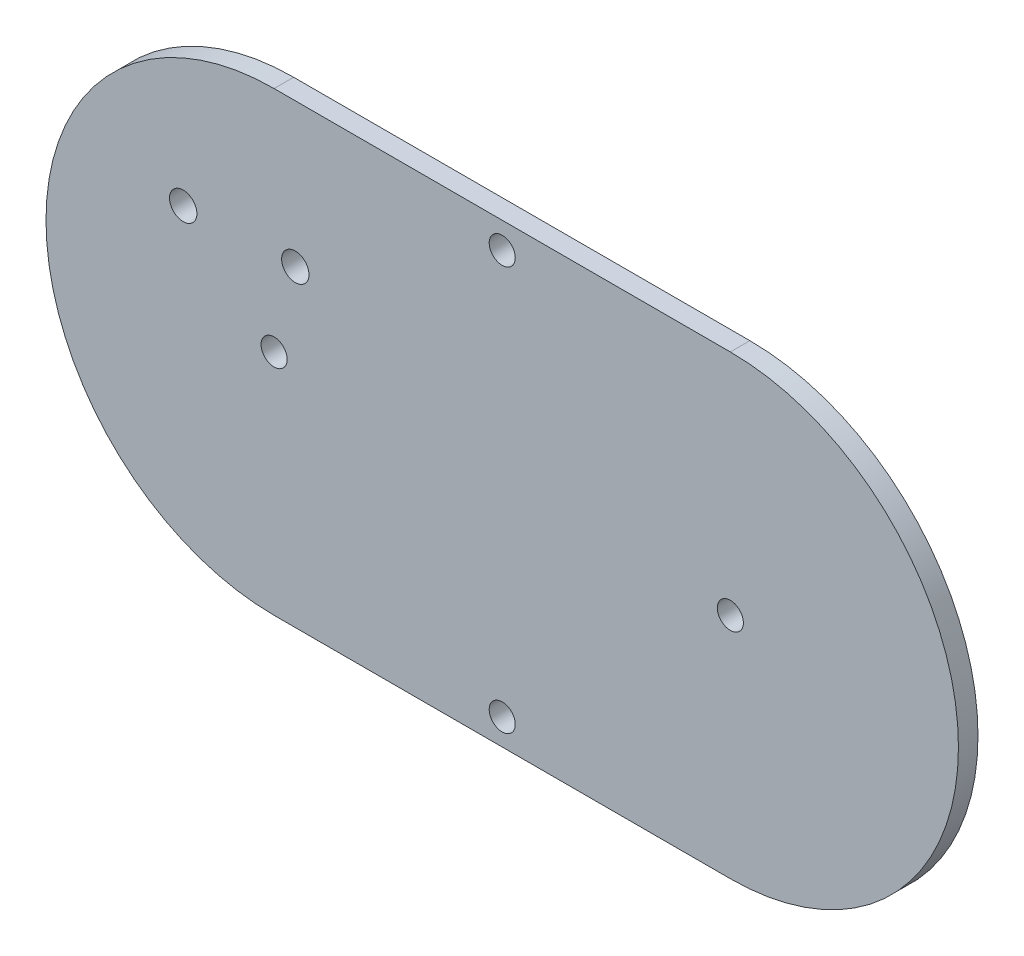
SolidWorks part; units mm, degrees
ref_plane "Front Plane" through (0, 0, 0) normal (0, 0, 1) x (1, 0, 0)
ref_plane "Top Plane" through (0, 0, 0) normal (0, 1, 0) x (1, 0, 0)
ref_plane "Right Plane" through (0, 0, 0) normal (1, 0, 0) x (0, 0, -1)
sketch "Sketch1" plane through (0, 0, 0) normal (0, 0, 1) x (1, 0, 0)
  line L0 (278.5146, 346.2873) -> (278.5146, 276.2873) construction
  line L1 (243.5146, 346.2873) -> (313.5146, 346.2873)
  line L3 (243.5146, 276.2873) -> (313.5146, 276.2873)
  line L12 (208.5146, 311.2873) -> (348.5146, 311.2873) construction
  arc A0 (243.5146, 346.2873) -> (243.5146, 276.2873) centre (243.5146, 311.2873) ccw
  arc A1 (313.5146, 346.2873) -> (313.5146, 276.2873) centre (313.5146, 311.2873) cw
  circle A2 centre (243.5146, 311.2873) radius 2
  circle A3 centre (313.5146, 311.2873) radius 2
  circle A4 centre (246.7646, 324.2256) radius 2.1
  circle A5 centre (229.5646, 323.7256) radius 2.1
  circle A6 centre (278.5146, 342.2873) radius 2
  circle A7 centre (278.5146, 280.2873) radius 2
  point P45 (278.5146, 342.2873)
  dimension "D3" = 4
  dimension "D4" = 4
  dimension "D7" = 4
  dimension "D1" = 70
  dimension "D2" = 70
  dimension "D5" = 12.9383
  dimension "D6" = 4
  dimension "D9" = 12.4383
  dimension "D10" = 17.2
extrude "Boss-Extrude1" add sketch "Sketch1" along normal blind 3
